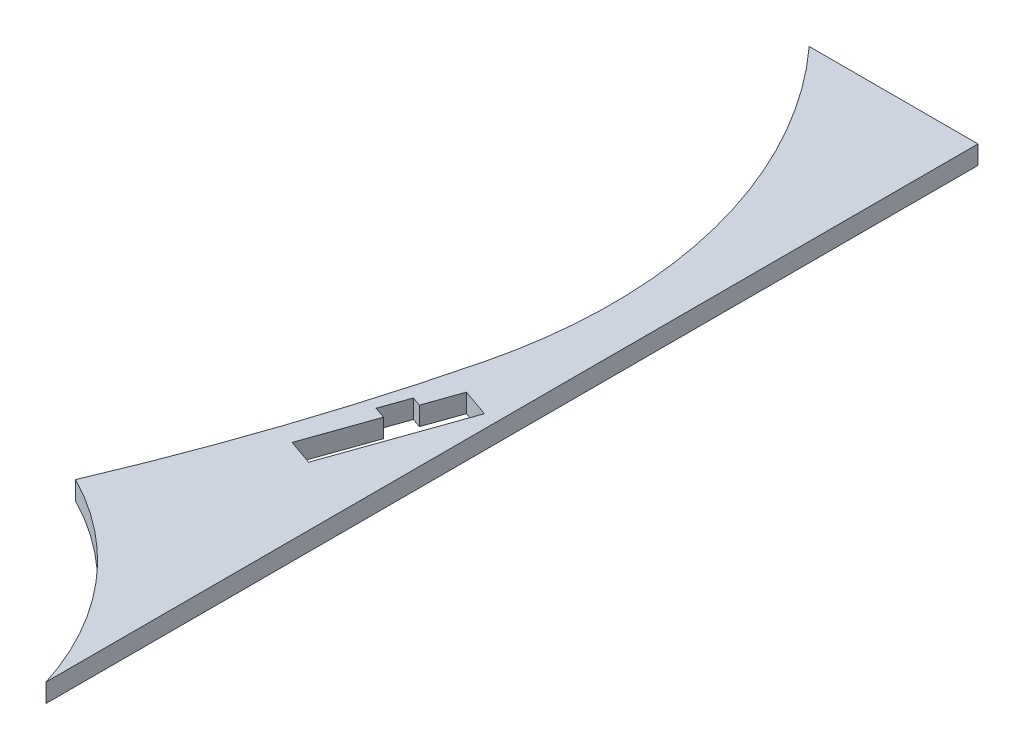
SolidWorks part; units mm, degrees
material "Acrylic (Medium-high impact)"
ref_plane "Front Plane" through (0, 0, 0) normal (0, 0, 1) x (1, 0, 0)
ref_plane "Top Plane" through (0, 0, 0) normal (0, 1, 0) x (1, 0, 0)
ref_plane "Right Plane" through (0, 0, 0) normal (1, 0, 0) x (0, 0, -1)
sketch "Sketch1" plane through (0, 0, 0) normal (0, 1, 0) x (1, 0, 0)
  line L62 (-86.9348, 33.6872) -> (-73.7224, 64.7656) construction
  line L68 (0, 169.3886) -> (0, 0)
  line L74 (-19.05, 0) -> (0, 0)
  line L84 (-19.05, 317.5) -> (-19.05, 0) construction
  line L85 (0, 317.5) -> (-19.05, 317.5) construction
  line L86 (0, 169.3886) -> (-19.05, 169.3886)
  line L87 (-19.05, 169.3886) -> (-19.05, 317.5)
  line L89 (0, 317.5) -> (0, 169.3886) construction
  line L90 (-19.05, 317.5) -> (-76.5548, 317.5)
  arc A12 (-73.7224, 64.7656) -> (-38.8765, 169.3886) centre (-704.9171, 333.1067) ccw
  arc A13 (-73.7224, 64.7656) -> (-19.05, 0) centre (-123.825, -32.9878) cw
  arc A15 (-38.8765, 169.3886) -> (-76.5548, 317.5) centre (-196.51, 208.1362) ccw
  dimension "D5" = 162.3259
  dimension "D2" = 33.7703
  dimension "D8" = 57.5048
  dimension "D9" = 109.8453
  dimension "D4" = 19.05
  dimension "D7" = 23.032
  dimension "D6" = 685.8671
  dimension "D3" = 169.3886
  dimension "D1" = 317.5
extrude "Boss-Extrude1" add sketch "Sketch1" along normal blind 6.35
sketch "Sketch3" plane through (0, 6.35, 0) normal (0, 1, 0) x (1, 0, 0)
  line L0 (-19.05, 0) -> (0, 0) construction
  line L1 (0, 169.3886) -> (-19.05, 169.3886)
  line L2 (0, 169.3886) -> (0, 0)
  line L3 (0, 0) -> (-19.05, 0)
  line L4 (-19.05, 169.3886) -> (-19.05, 0)
  line L5 (-19.05, 169.3886) -> (-19.05, 317.5) construction
extrude "Cut-Extrude3" cut sketch "Sketch3" against normal through all
sketch "Sketch2" plane through (0, 6.35, 0) normal (0, 1, 0) x (1, 0, 0)
  line L0 (-39.808, 110.8665) -> (-45.7961, 112.9797) construction
  line L1 (-39.0895, 110.6129) -> (-39.808, 110.8665) construction
  line L2 (-33.1811, 129.6451) -> (-39.1692, 131.7583) construction
  line L3 (-32.4626, 129.3915) -> (-33.1811, 129.6451) construction
  line L4 (-39.0895, 110.6129) -> (-32.4626, 129.3915) construction
  line L5 (-19.05, 317.5) -> (-76.5548, 317.5)
  line L6 (-19.05, 0) -> (-19.05, 317.5)
  line L19 (-19.05, 317.5) -> (-76.5548, 317.5)
  line L20 (-19.05, 0) -> (-19.05, 317.5)
  line L24 (-39.808, 110.8665) -> (-45.7961, 112.9797) construction
  line L25 (-39.0895, 110.6129) -> (-39.808, 110.8665) construction
  line L26 (-33.1811, 129.6451) -> (-39.1692, 131.7583) construction
  line L27 (-32.4626, 129.3915) -> (-33.1811, 129.6451) construction
  line L28 (-39.0895, 110.6129) -> (-32.4626, 129.3915) construction
  line L29 (-45.7961, 112.9797) -> (-46.5147, 113.2332) construction
  line L30 (-45.7961, 112.9797) -> (-46.5147, 113.2332) construction
  line L31 (-39.5835, 132.8741) -> (-46.5147, 113.2332) construction
  line L32 (-39.5835, 132.8741) -> (-46.5147, 113.2332) construction
  line L33 (-38.8649, 132.6205) -> (-39.5835, 132.8741) construction
  line L34 (-38.8649, 132.6205) -> (-39.5835, 132.8741) construction
  line L35 (-39.1692, 131.7583) -> (-38.8649, 132.6205) construction
  line L37 (-40.6636, 137.0262) -> (-33.1665, 134.3805) construction
  line L38 (-31.1412, 135.3493) -> (-25.3681, 151.7087) construction
  line L39 (-30.8278, 155.3189) -> (-26.3368, 153.734) construction
  line L40 (-36.5132, 143.9788) -> (-32.8532, 154.3501) construction
  line L41 (-40.6636, 137.0262) -> (-33.1665, 134.3805) construction
  line L42 (-31.1412, 135.3493) -> (-25.3681, 151.7087) construction
  line L43 (-30.8278, 155.3189) -> (-26.3368, 153.734) construction
  line L44 (-36.5132, 143.9788) -> (-32.8532, 154.3501) construction
  line L46 (-40.6636, 137.0262) -> (-42.2924, 137.601) construction
  line L47 (-42.2924, 137.601) -> (-39.6509, 145.0861) construction
  line L48 (-39.6509, 145.0861) -> (-36.5132, 143.9788) construction
  line L49 (-42.2924, 137.601) -> (-39.6509, 145.0861) construction
  line L50 (-39.1641, 109.5618) -> (-23.5436, 153.8257)
  line L51 (-23.5436, 153.8257) -> (-32.9448, 157.1434)
  line L52 (-32.9448, 157.1434) -> (-37.1331, 145.275)
  line L53 (-37.1331, 145.275) -> (-40.2709, 146.3823)
  line L54 (-40.2709, 146.3823) -> (-43.5886, 136.981)
  line L55 (-43.5886, 136.981) -> (-39.6963, 135.6075)
  line L56 (-39.6963, 135.6075) -> (-47.8109, 112.6133)
  line L57 (-47.8109, 112.6133) -> (-39.1641, 109.5618)
  line L58 (-28.5823, 154.5264) -> (-28.2442, 155.4845) construction
  line L59 (-28.2546, 143.529) -> (-27.2966, 143.1909) construction
  line L60 (-34.6832, 149.1645) -> (-35.6412, 149.5026) construction
  line L61 (-40.9716, 141.3435) -> (-41.9297, 141.6817) construction
  line L62 (-39.6509, 145.0861) -> (-39.3128, 146.0442) construction
  line L63 (-40.6636, 137.0262) -> (-41.0017, 136.0681) construction
  line L64 (-43.0491, 123.0537) -> (-44.0072, 123.3918) construction
  line L65 (-42.8021, 111.9231) -> (-43.1402, 110.965) construction
  arc A3 (-33.1665, 134.3805) -> (-31.1412, 135.3493) centre (-32.6383, 135.8776) ccw construction
  arc A4 (-25.3681, 151.7087) -> (-26.3368, 153.734) centre (-26.8651, 152.237) ccw construction
  arc A8 (-30.8278, 155.3189) -> (-32.8532, 154.3501) centre (-31.3561, 153.8218) ccw construction
  arc A9 (-19.05, 0) -> (-73.7224, 64.7656) centre (-123.825, -32.9878) ccw
  arc A10 (-73.7224, 64.7656) -> (-38.8765, 169.3886) centre (-704.9171, 333.1067) ccw
  arc A11 (-38.8765, 169.3886) -> (-76.5548, 317.5) centre (-196.51, 208.1362) ccw
  arc A12 (-19.05, 0) -> (-73.7224, 64.7656) centre (-123.825, -32.9878) ccw
  arc A13 (-73.7224, 64.7656) -> (-38.8765, 169.3886) centre (-704.9171, 333.1067) ccw
  arc A14 (-38.8765, 169.3886) -> (-76.5548, 317.5) centre (-196.51, 208.1362) ccw
  circle A15 centre (-30.2733, 150.9751) radius 1.8415 construction
  circle A16 centre (-34.4996, 138.999) radius 1.8415 construction
  arc A17 (-33.1665, 134.3805) -> (-31.1412, 135.3493) centre (-32.6383, 135.8776) ccw construction
  arc A18 (-25.3681, 151.7087) -> (-26.3368, 153.734) centre (-26.8651, 152.237) ccw construction
  arc A19 (-30.8278, 155.3189) -> (-32.8532, 154.3501) centre (-31.3561, 153.8218) ccw construction
  circle A20 centre (-30.2733, 150.9751) radius 1.8415 construction
  circle A21 centre (-34.4996, 138.999) radius 1.8415 construction
  point P41 (-28.2442, 155.4845)
  dimension "D2" = 1.016
  dimension "D1" = 0
extrude "Cut-Extrude2" cut sketch "Sketch2" against normal through all contours L54 L55 L56 L57 L50 L51 L52 L53
